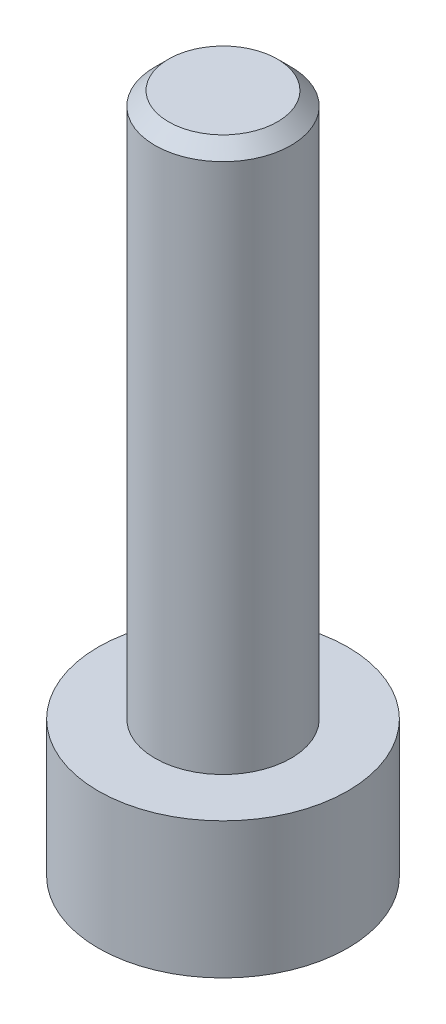
SolidWorks part; units mm, degrees
ref_plane "前视基准面" through (0, 0, 0) normal (0, 0, 1) x (1, 0, 0)
ref_plane "上视基准面" through (0, 0, 0) normal (0, 1, 0) x (1, 0, 0)
ref_plane "右视基准面" through (0, 0, 0) normal (1, 0, 0) x (0, 0, -1)
sketch "草图1" plane through (0, 0, 0) normal (0, 1, 0) x (1, 0, 0)
  circle A0 centre (0, 0) radius 2.75
  dimension "D1" = 5.5
extrude "凸台-拉伸1" add sketch "草图1" along normal blind 3
sketch "草图2" plane through (0, 3, 0) normal (0, 1, 0) x (1, 0, 0)
  circle A0 centre (0, 0) radius 1.5
  dimension "D1" = 3
sketch "草图3" plane through (0, 0, 0) normal (0, -1, 0) x (1, 0, 0)
  line L1 (0, 1.25) -> (-1.0825, 0.625)
  line L2 (-1.0825, 0.625) -> (-1.0825, -0.625)
  line L3 (-1.0825, -0.625) -> (0, -1.25)
  line L4 (0, -1.25) -> (1.0825, -0.625)
  line L5 (1.0825, -0.625) -> (1.0825, 0.625)
  line L6 (1.0825, 0.625) -> (0, 1.25)
  circle A0 centre (0, 0) radius 1.0825 construction
  dimension "D1" = 2.5
extrude "切除-拉伸1" cut sketch "草图3" against normal blind 1.5
extrude "凸台-拉伸2" add sketch "草图2" along normal blind 12
cosmetic thread "装饰螺纹线1" parameters "D2"=2
chamfer "倒角1" distance 0.3 angle 45 1 edges at (0, 15, 1.5)
